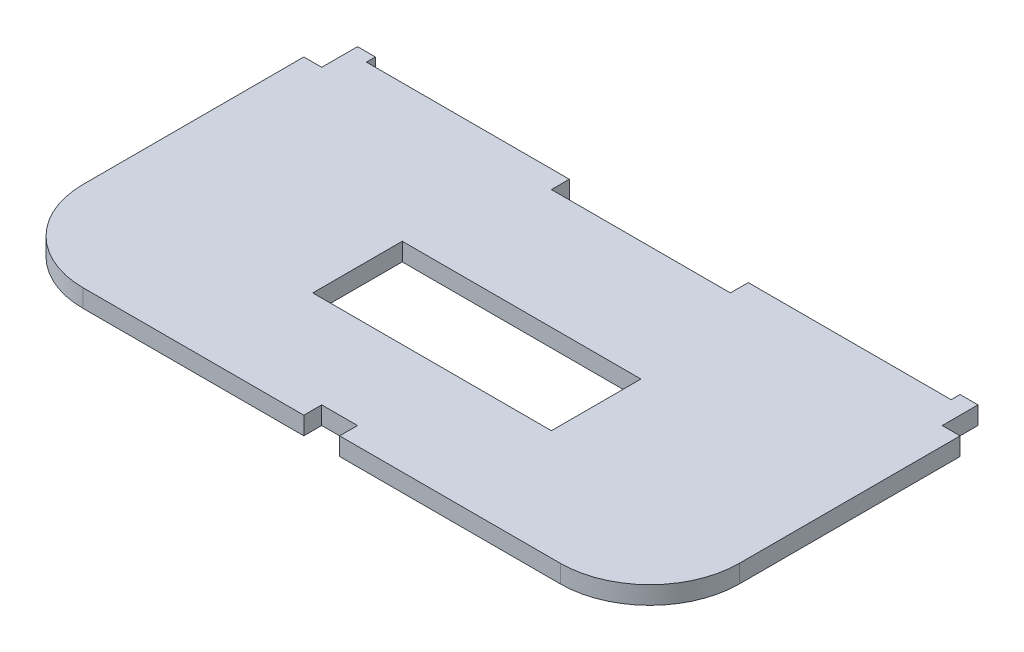
SolidWorks part; units mm, degrees
ref_plane "Спереди" through (0, 0, 0) normal (0, 0, 1) x (1, 0, 0)
ref_plane "Сверху" through (0, 0, 0) normal (0, 1, 0) x (1, 0, 0)
ref_plane "Справа" through (0, 0, 0) normal (1, 0, 0) x (0, 0, -1)
other "Configuration Table"
sketch "Эскиз3" plane through (0, 0, 0) normal (0, 1, 0) x (1, 0, 0)
  line L0 (0, 52) -> (3, 52)
  line L1 (0, 0) -> (52, 0)
  line L2 (0, 0) -> (0, 52)
  line L3 (3, 58) -> (6, 58)
  line L4 (110, 0) -> (110, 52)
  line L5 (3, 52) -> (3, 58)
  line L6 (55, 58) -> (55, -2.2073) construction
  line L7 (110, 52) -> (107, 52)
  line L8 (107, 52) -> (107, 58)
  line L9 (55, 3) -> (52, 3)
  line L10 (52, 3) -> (55, 3)
  line L11 (55, 3) -> (58, 3)
  line L12 (52, 3) -> (52, 0)
  line L13 (58, 3) -> (58, 0)
  line L14 (58, 0) -> (110, 0)
  line L15 (40, 56.5) -> (40, 53.5)
  line L16 (40, 53.5) -> (70, 53.5)
  line L17 (70, 53.5) -> (70, 56.5)
  line L18 (104, 58) -> (107, 58)
  line L19 (6, 58) -> (6, 56.5)
  line L20 (35, 33.5) -> (75, 33.5)
  line L21 (35, 33.5) -> (35, 18.5)
  line L22 (35, 18.5) -> (75, 18.5)
  line L23 (75, 33.5) -> (75, 18.5)
  line L24 (6, 56.5) -> (40, 56.5)
  line L25 (70, 56.5) -> (104, 56.5)
  line L26 (104, 56.5) -> (104, 58)
  dimension "D2" = 110
  dimension "D3" = 6
  dimension "D4" = 3
  dimension "D5" = 30
  dimension "D6" = 15
  dimension "D7" = 40
  dimension "D8" = 20
  dimension "D9" = 58
  dimension "D10" = 1.5
  dimension "D11" = 3
  dimension "D12" = 4.5
  dimension "D13" = 3
extrude "Бобышка-Вытянуть2" add sketch "Эскиз3" along normal blind 3 contours L6 L3 L5 L0 L2 L1 L12 L9 | L3 L6 L11 L13 L14 L4 L7 L8
fillet "Fillet1" radius 15 2 edges at (110, 1.5, 0) (0, 1.5, 0)
